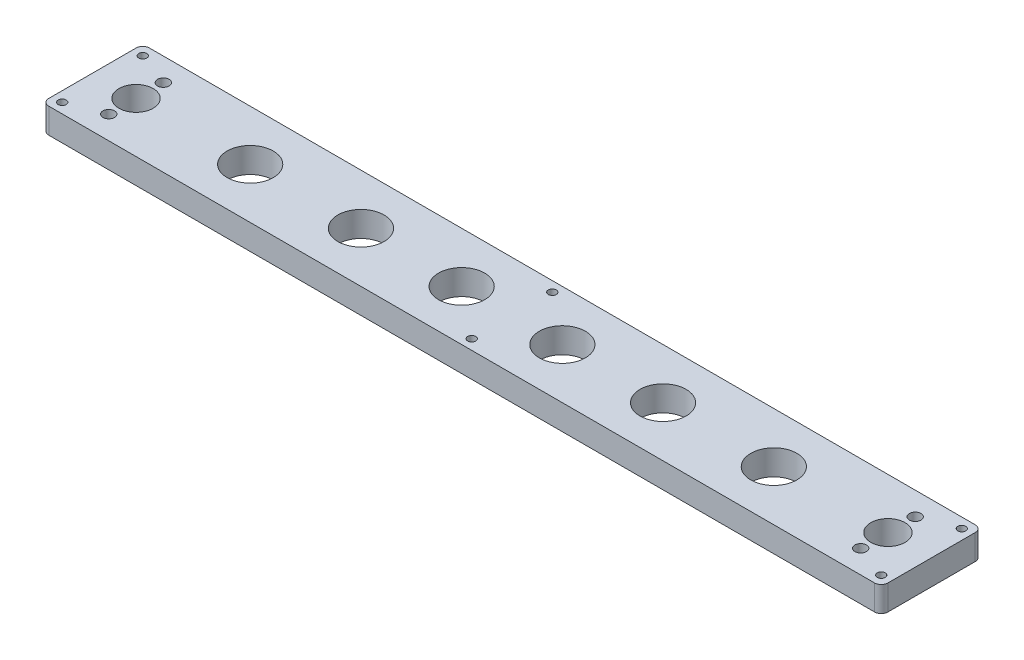
SolidWorks part; units mm, degrees
material "Acrylic (Medium-high impact)"
ref_plane "Front Plane" through (0, 0, 0) normal (0, 0, 1) x (1, 0, 0)
ref_plane "Top Plane" through (0, 0, 0) normal (0, 1, 0) x (1, 0, 0)
ref_plane "Right Plane" through (0, 0, 0) normal (1, 0, 0) x (0, 0, -1)
sketch "Sketch1" plane through (0, 0, 0) normal (0, 1, 0) x (1, 0, 0)
  line L1 (-158.75, -19.05) -> (158.75, -19.05)
  line L2 (-158.75, -19.05) -> (-158.75, 19.05)
  line L3 (-158.75, 19.05) -> (158.75, 19.05)
  line L4 (158.75, -19.05) -> (158.75, 19.05)
  line L5 (-158.75, -19.05) -> (158.75, 19.05) construction
  line L6 (-158.75, 19.05) -> (158.75, -19.05) construction
  point P0 (0, 0)
  dimension "D1" = 317.5
  dimension "D2" = 38.1
extrude "Boss-Extrude1" add sketch "Sketch1" along normal mid plane 9.525
sketch "Sketch2" plane through (0, 4.7625, 0) normal (0, 1, 0) x (1, 0, 0)
  line L0 (-133.35, 0) -> (0, 0) construction
  line L1 (-142.24, -10.3187) -> (-142.24, 10.3187) construction
  line L2 (-158.75, 19.05) -> (-158.75, -19.05) construction
  line L4 (142.24, -10.3187) -> (142.24, 10.3187) construction
  line L5 (158.75, -19.05) -> (158.75, 19.05) construction
  circle A0 centre (-142.24, 0) radius 10.16 construction
  circle A1 centre (-99.06, 0) radius 4.4196
  circle A2 centre (-57.15, 0) radius 4.4196
  circle A3 centre (-19.05, 0) radius 4.4196
  circle A4 centre (19.05, 0) radius 4.4196
  circle A5 centre (57.15, 0) radius 4.4196
  circle A6 centre (142.24, 0) radius 10.16 construction
  circle A7 centre (-142.24, 0) radius 6.477
  circle A8 centre (-142.24, -10.3187) radius 2.1908
  circle A9 centre (-142.24, 10.3187) radius 2.1908
  circle A10 centre (142.24, 0) radius 6.477
  circle A11 centre (142.24, -10.3187) radius 2.1908
  circle A12 centre (142.24, 10.3187) radius 2.1908
  circle A13 centre (99.06, 0) radius 4.4196
  point P3 (-158.75, 0)
  point P28 (-142.24, -8.128)
  point P29 (-142.24, 8.128)
  point P30 (-142.24, 0)
  point P37 (142.24, -8.128)
  point P38 (142.24, 8.128)
  point P39 (142.24, 0)
  dimension "D1" = 20.32
  dimension "D5" = 8.8392
  dimension "D9" = 12.954
  dimension "D10" = 4.3815
  dimension "D12" = 12.954
  dimension "D13" = 4.3815
  dimension "D2" = 43.18
  dimension "D3" = 16.51
  dimension "D4" = 38.1
  dimension "D6" = 43.18
  dimension "D7" = 38.1
  dimension "D8" = 38.1
  dimension "D11" = 10.3187
  dimension "D14" = 10.3187
  dimension "D15" = 19.05
  dimension "D16" = 16.51
extrude "Cut-Extrude1" cut sketch "Sketch2" against normal through all
sketch "Sketch3" plane through (0, 4.7625, 0) normal (0, 1, 0) x (1, 0, 0)
  line L0 (-158.75, 19.05) -> (-158.75, -19.05) construction
  line L1 (154.94, -15.24) -> (-154.94, -15.24) construction
  line L2 (154.94, -15.24) -> (154.94, 15.24) construction
  line L3 (154.94, 15.24) -> (-154.94, 15.24) construction
  line L4 (-154.94, -15.24) -> (-154.94, 15.24) construction
  line L5 (154.94, -15.24) -> (-154.94, 15.24) construction
  line L6 (154.94, 15.24) -> (-154.94, -15.24) construction
  line L7 (158.75, 19.05) -> (-158.75, 19.05) construction
  circle A0 centre (-154.94, 15.24) radius 1.5113
  circle A1 centre (-154.94, -15.24) radius 1.5113
  circle A2 centre (154.94, -15.24) radius 1.5113
  circle A3 centre (154.94, 15.24) radius 1.5113
  circle A4 centre (0, 15.24) radius 1.5113
  circle A5 centre (0, -15.24) radius 1.5113
  point P0 (0, 0)
  dimension "D1" = 3.0226
  dimension "D2" = 3.81
  dimension "D3" = 3.81
extrude "Cut-Extrude2" cut sketch "Sketch3" against normal through all
fillet "Fillet1" radius 2.54 4 edges at (158.75, 0, 19.05) (-158.75, 0, 19.05) (158.75, 0, -19.05) (-158.75, 0, -19.05)
sketch "Sketch4" plane through (0, 4.7625, 0) normal (0, 1, 0) x (1, 0, 0)
  circle A0 centre (99.06, 0) radius 8.7313
  circle A1 centre (-99.06, 0) radius 8.7313
  circle A2 centre (-57.15, 0) radius 8.7313
  circle A3 centre (-19.05, 0) radius 8.7313
  circle A4 centre (19.05, 0) radius 8.7312
  circle A5 centre (57.15, 0) radius 8.7313
  dimension "D2" = 17.4625
extrude "Cut-Extrude3" cut sketch "Sketch4" against normal through all
sketch "Sketch5" plane through (0, 4.7625, 0) normal (0, 1, 0) x (1, 0, 0)
  line L0 (158.75, -16.51) -> (158.75, 16.51) construction
  line L1 (-27.686, -12.7) -> (73.914, -12.7) construction
  line L2 (-27.686, -12.7) -> (-27.686, 12.7) construction
  line L3 (-27.686, 12.7) -> (73.914, 12.7) construction
  line L4 (73.914, -12.7) -> (73.914, 12.7) construction
  line L5 (-27.686, -12.7) -> (73.914, 12.7) construction
  line L6 (-27.686, 12.7) -> (73.914, -12.7) construction
  point P0 (23.114, 0)
  point P7 (0, 0)
  dimension "D1" = 84.836
  dimension "D2" = 101.6
  dimension "D3" = 25.4
